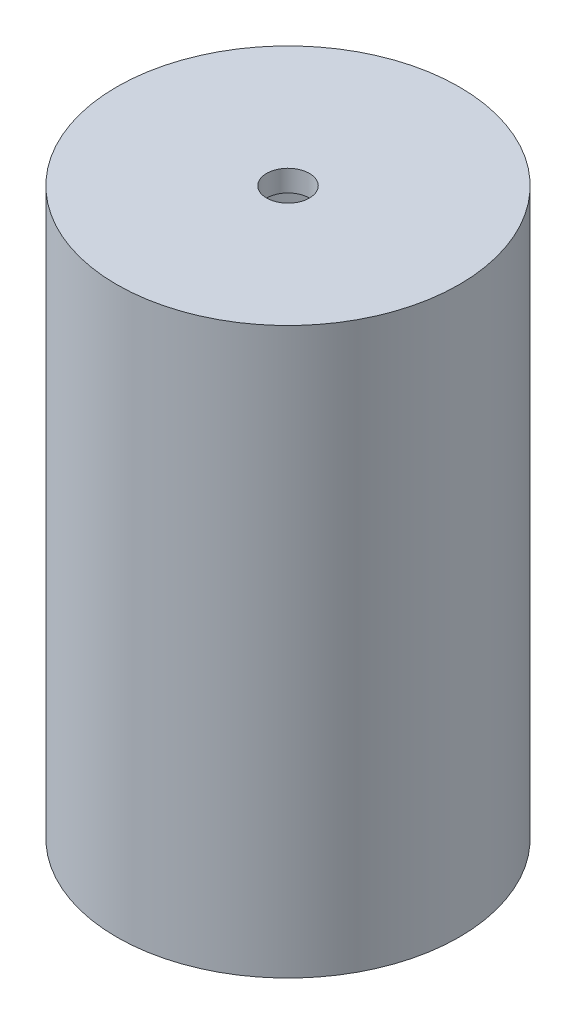
SolidWorks part; units mm, degrees
other "Markup1"
sketch "Sketch2" plane through (-8, 26.5, 8) normal (-0.0749, 0.6705, 0.7381) x (0.9552, -0.1642, 0.2461)
ref_plane "Front Plane" through (0, 0, 0) normal (0, 0, 1) x (1, 0, 0)
ref_plane "Top Plane" through (0, 0, 0) normal (0, 1, 0) x (1, 0, 0)
ref_plane "Right Plane" through (0, 0, 0) normal (1, 0, 0) x (0, 0, -1)
sketch "Sketch1" plane through (0, 0, 0) normal (0, 1, 0) x (1, 0, 0)
  circle A0 centre (0, 0) radius 8
  dimension "D1" = 16
extrude "Boss-Extrude1" add sketch "Sketch1" along normal blind 26.4
shell "Shell7" thickness 1
sketch "Sketch4" plane through (0, 26.4, 0) normal (0, 1, 0) x (1, 0, 0)
  circle A0 centre (0, 0) radius 1
  dimension "D1" = 2
extrude "Cut-Extrude1" cut sketch "Sketch4" against normal blind 3
sketch "Sketch6" plane through (0, 0, 0) normal (0, -1, 0) x (1, 0, 0)
  circle A0 centre (0, 0) radius 0.8
  dimension "D1" = 1.6
extrude "Cut-Extrude2" cut sketch "Sketch6" against normal blind 6
